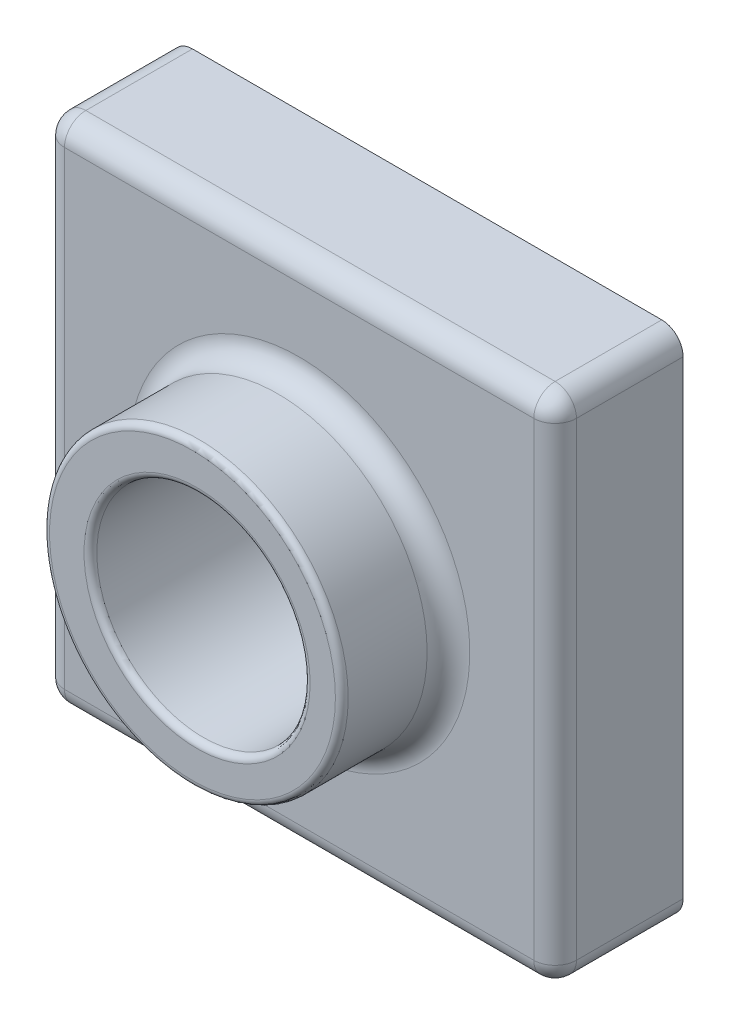
SolidWorks part; units mm, degrees
ref_plane "Front Plane" through (0, 0, 0) normal (0, 0, 1) x (1, 0, 0)
ref_plane "Top Plane" through (0, 0, 0) normal (0, 1, 0) x (1, 0, 0)
ref_plane "Right Plane" through (0, 0, 0) normal (1, 0, 0) x (0, 0, -1)
sketch "Sketch1" plane through (0, 0, 0) normal (0, 0, 1) x (1, 0, 0)
  line L1 (0, 0) -> (120, 0)
  line L2 (0, 0) -> (0, 120)
  line L3 (0, 120) -> (120, 120)
  line L4 (120, 0) -> (120, 120)
  line L5 (0, 0) -> (120, 120) construction
  line L6 (0, 120) -> (120, 0) construction
  point P0 (60, 60)
  point P5 (0, 0)
  point P6 (120, 105.703)
  dimension "D1" = 120
  dimension "D2" = 120
extrude "Boss-Extrude1" add sketch "Sketch1" along normal blind 30
sketch "Sketch2" plane through (0, 0, 30) normal (0, 0, 1) x (1, 0, 0)
  circle A0 centre (60, 60) radius 35
  dimension "D1" = 70
  dimension "D2" = 60
  dimension "D3" = 60
extrude "Boss-Extrude2" add sketch "Sketch2" along normal blind 25
sketch "Sketch5" plane through (0, 0, 55) normal (0, 0, 1) x (1, 0, 0)
  circle A0 centre (61.0777, 60) radius 25
  dimension "D1" = 50
extrude "Cut-Extrude1" cut sketch "Sketch5" against normal through all
fillet "Fillet1" radius 5 9 edges at (60, 0, 30) (0, 60, 30) (60, 120, 30) (120, 60, 30) (95, 60, 30) (120, 0, 15) (120, 120, 15) (0, 120, 15) (0, 0, 15)
fillet "Fillet2" radius 1.5 2 edges at (95, 60, 55) (86.0777, 60, 55)
shell "Shell1" thickness 2
